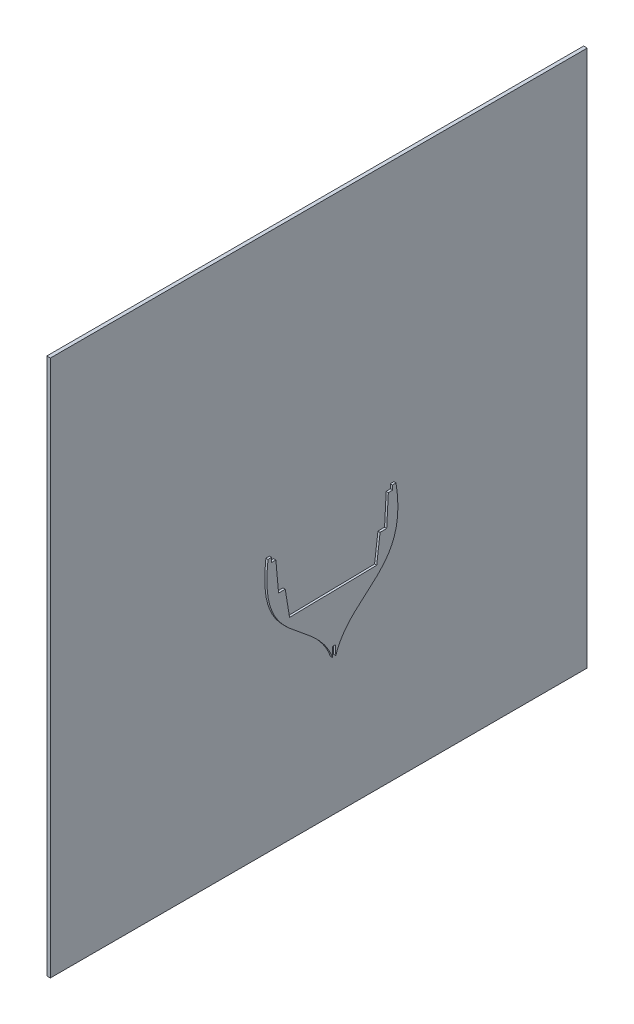
SolidWorks part; units mm, degrees
ref_plane "Plan de face" through (0, 0, 0) normal (0, 0, 1) x (1, 0, 0)
ref_plane "Plan de dessus" through (0, 0, 0) normal (0, 1, 0) x (1, 0, 0)
ref_plane "Plan de droite" through (0, 0, 0) normal (1, 0, 0) x (0, 0, -1)
sketch "Esquisse1" plane through (0, 0, 0) normal (0, 0, 1) x (1, 0, 0)
  point P0 (-20, 0)
  dimension "D1" = 20
sketch3d "Esquisse3D1"
  line L1 (-20, 1121.2893, 777.275) -> (-20, 1121.2893, -722.725)
  line L2 (-20, 1121.2893, 777.275) -> (-20, -378.7107, 777.275)
  line L3 (-20, -378.7107, 777.275) -> (-20, -378.7107, -722.725)
  line L4 (-20, 1121.2893, -722.725) -> (-20, -378.7107, -722.725)
  dimension "D1" = 1500
  dimension "D2" = 1500
extrude "Boss.-Extru.2" add sketch "Esquisse3D1" along direction (1, 0, 0) on the side of the normal blind 10 contours L2 L1 L4 L3
sketch "Esquisse4" plane through (-10, 0, 0) normal (1, 0, 0) x (0, 0, -1)
  line L0 (0, 0) -> (-7.701, 425.1082) construction
  line L1 (169.3944, 339.9131) -> (-188.5193, 333.4294) construction
  line L2 (-187.2006, 249.23) -> (169.0622, 255.6839) construction
  line L3 (-144.268, 175.2448) -> (126.4811, 180.1495) construction
sketch "Esquisse5" plane through (0, 0, 0) normal (1, 0, 0) x (0, 0, -1)
  line L0 (-7.701, 425.1082) -> (0, 0) construction
  line L2 (0, 0) -> (1.9272, 16.0995) construction
  line L3 (1.9272, 16.0995) -> (26.7598, 168.4293) construction
  line L4 (26.7598, 168.4293) -> (213.3674, 100.6995) construction
  line L5 (213.3674, 100.6995) -> (172.4622, 352.3324) construction
  line L8 (172.4622, 352.3324) -> (162.4622, 352.1513)
  line L9 (162.4622, 352.1513) -> (163.2237, 339.8013)
  line L10 (169.3944, 339.9131) -> (-188.5193, 333.4294) construction
  line L11 (163.2237, 339.8013) -> (151.0185, 339.5802)
  line L12 (151.0185, 339.5802) -> (146.473, 255.2747)
  line L13 (-187.2006, 249.23) -> (169.0622, 255.6839) construction
  line L14 (146.473, 255.2747) -> (127.9947, 254.9399)
  line L15 (127.9947, 254.9399) -> (118.5267, 180.0054)
  line L16 (-144.268, 175.2448) -> (126.4811, 180.1495) construction
  line L17 (118.5267, 180.0054) -> (-124.9685, 175.5944)
  line L18 (0, 0) -> (-2.5091, 16.0191) construction
  line L19 (-2.5091, 16.0191) -> (-32.8425, 167.3496) construction
  line L20 (-32.8425, 167.3496) -> (-216.8747, 92.9055) construction
  line L21 (-216.8747, 92.9055) -> (-185.1102, 345.8549) construction
  line L22 (-137.1444, 250.1368) -> (-124.9685, 175.5944)
  line L23 (-155.6226, 249.8021) -> (-137.1444, 250.1368)
  line L24 (-163.2186, 333.8877) -> (-155.6226, 249.8021)
  line L25 (-175.4239, 333.6666) -> (-163.2186, 333.8877)
  line L26 (-175.1102, 346.036) -> (-175.4239, 333.6666)
  line L27 (-185.1102, 345.8549) -> (-175.1102, 346.036)
  spline S0 degree 4 poles (0, 0) (1.9272, 16.0995) (26.7598, 168.4293) (213.3674, 100.6995) (172.4622, 352.3324) knots 0 0 0 0 0 1 1 1 1 1
  spline S1 degree 4 poles (0, 0) (-2.5091, 16.0191) (-32.8425, 167.3496) (-216.8747, 92.9055) (-185.1102, 345.8549) knots 0 0 0 0 0 1 1 1 1 1
  point P30 (-3.2209, 177.7999)
  dimension "D1" = 10
extrude "Boss.-Extru.3" add sketch "Esquisse5" along normal blind 6 separate body
sketch "Esquisse6" plane through (6, 0, 0) normal (1, 0, 0) x (0, 0, -1)
  line L0 (-4.835, 18.4122) -> (-5.3241, 45.4122)
  line L1 (-5.3241, 45.4122) -> (3.6759, 45.5752)
  line L2 (3.6759, 45.5752) -> (4.165, 18.5752)
  line L3 (4.165, 18.5752) -> (117.0633, -47.527)
  line L4 (117.0633, -47.527) -> (-85.2277, -65.22)
  line L5 (-85.2277, -65.22) -> (-4.835, 18.4122)
  line L6 (-4.835, 18.4122) -> (4.165, 18.5752) construction
  line L7 (-144.268, 175.2448) -> (126.4811, 180.1495) construction
  spline S0 degree 4 poles (-185.1102, 345.8549) (-216.8747, 92.9055) (-32.8425, 167.3496) (-2.5091, 16.0191) (0, 0) knots 0 0 0 0 0 1 1 1 1 1 construction
  spline S1 degree 4 poles (0, 0) (1.9272, 16.0995) (26.7598, 168.4293) (213.3674, 100.6995) (172.4622, 352.3324) knots 0 0 0 0 0 1 1 1 1 1 construction
  dimension "D1" = 9
  dimension "D2" = 27
extrude "Enlèv. mat.-Extru.1" cut sketch "Esquisse6" against normal blind 6
